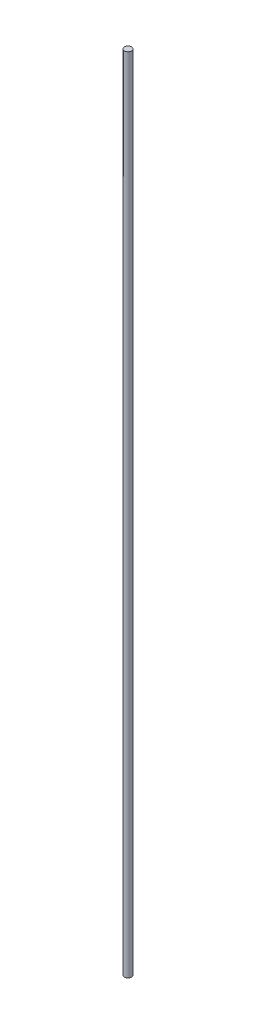
SolidWorks part; units mm, degrees
material "1060 Alloy"
ref_plane "Front Plane" through (0, 0, 0) normal (0, 0, 1) x (1, 0, 0)
ref_plane "Top Plane" through (0, 0, 0) normal (0, 1, 0) x (1, 0, 0)
ref_plane "Right Plane" through (0, 0, 0) normal (1, 0, 0) x (0, 0, -1)
sketch "Sketch1" plane through (0, 0, 0) normal (0, 1, 0) x (1, 0, 0)
  circle A0 centre (0, 0) radius 1.5
  dimension "D1" = 3
extrude "Boss-Extrude1" add sketch "Sketch1" along normal blind 340
